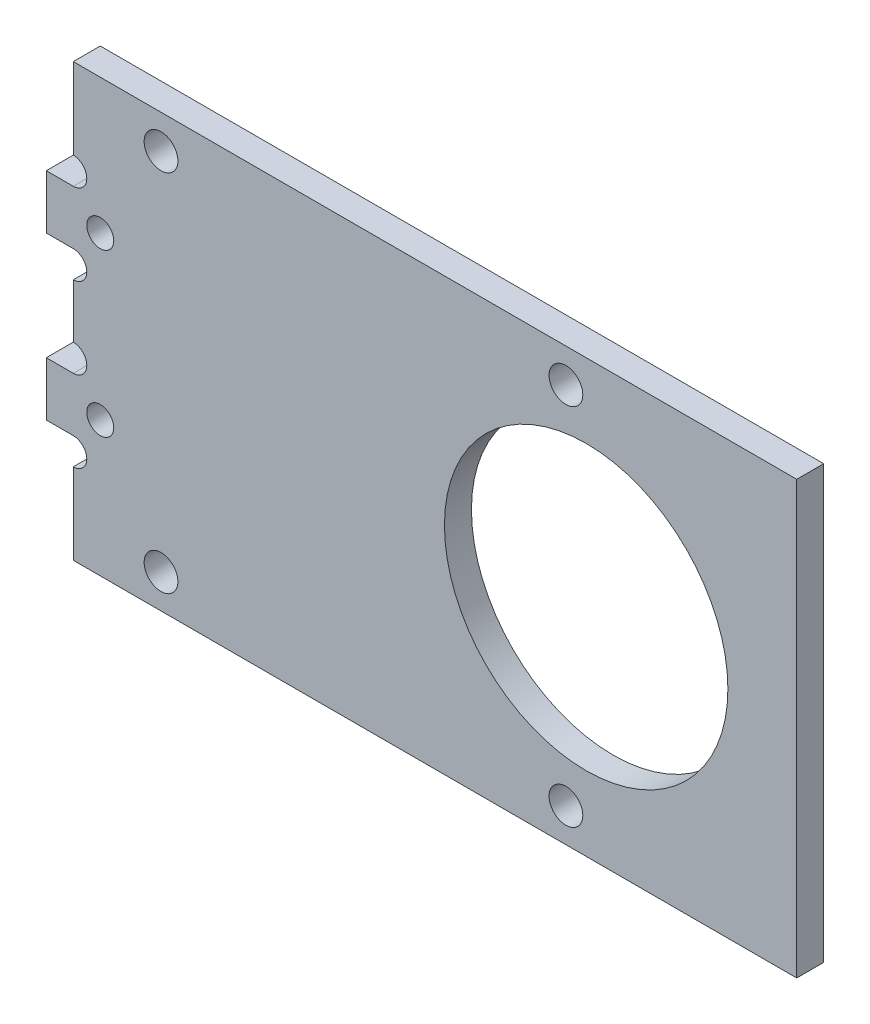
SolidWorks part; units mm, degrees
material "自訂玻璃纖維"
ref_plane "前基準面" through (0, 0, 0) normal (0, 0, 1) x (1, 0, 0)
ref_plane "上基準面" through (0, 0, 0) normal (0, 1, 0) x (1, 0, 0)
ref_plane "右基準面" through (0, 0, 0) normal (1, 0, 0) x (0, 0, -1)
sketch "草圖1" plane through (0, 0, 0) normal (0, 0, 1) x (1, 0, 0)
  line L0 (-8.8684, 14.8937) -> (-8.8684, 15.8937)
  line L1 (-7.8684, 15.8937) -> (43.7816, 15.8937)
  line L2 (-8.8684, 14.8937) -> (-8.8684, 9.8937)
  line L3 (-7.8684, -16.1063) -> (43.7816, -16.1063)
  line L4 (44.7316, 14.8937) -> (44.7316, -15.1063)
  line L5 (-8.8684, 15.8937) -> (-7.8684, 15.8937)
  line L6 (44.7316, 14.8937) -> (44.7316, 15.8937)
  line L7 (44.7316, 15.8937) -> (43.7816, 15.8937)
  line L8 (44.7316, -15.1063) -> (44.7316, -16.1063)
  line L9 (44.7316, -16.1063) -> (43.7816, -16.1063)
  line L10 (-8.8684, -15.1063) -> (-8.8684, -16.1063)
  line L11 (-8.8684, -16.1063) -> (-7.8684, -16.1063)
  line L12 (-8.8684, 1.8937) -> (-8.8684, -2.1063)
  line L13 (-8.8684, 7.8937) -> (-10.8684, 7.8937)
  line L14 (-8.8684, -8.1063) -> (-10.8684, -8.1063)
  line L15 (-8.8684, 3.8937) -> (-10.8684, 3.8937)
  line L16 (-10.8684, 7.8937) -> (-10.8684, 3.8937)
  line L17 (-8.8684, -4.1063) -> (-10.8684, -4.1063)
  line L18 (-10.8684, -4.1063) -> (-10.8684, -8.1063)
  line L19 (-8.8684, -10.1063) -> (-8.8684, -15.1063)
  arc A0 (-8.8684, 7.8937) -> (-8.8684, 9.8937) centre (-8.8684, 8.8937) ccw
  circle A1 centre (-6.8684, 5.8937) radius 1
  circle A2 centre (-6.8684, -6.1063) radius 1
  arc A3 (-8.8684, 3.8937) -> (-8.8684, 1.8937) centre (-8.8684, 2.8937) cw
  arc A4 (-8.8684, -8.1063) -> (-8.8684, -10.1063) centre (-8.8684, -9.1063) cw
  arc A5 (-8.8684, -4.1063) -> (-8.8684, -2.1063) centre (-8.8684, -3.1063) ccw
  circle A6 centre (-2.3684, 13.3937) radius 1.25
  circle A7 centre (-2.3684, -13.6063) radius 1.25
  circle A8 centre (27.6316, 13.3937) radius 1.25
  circle A9 centre (27.6316, -13.6063) radius 1.25
  circle A10 centre (29.1316, -0.1063) radius 10.5
  point P10 (-8.8684, -16.1063)
  point P15 (44.7316, 15.8937)
  point P18 (-8.8684, 15.8937)
  dimension "D2" = 53.6
  dimension "D3" = 2
  dimension "D4" = 4
  dimension "D5" = 12
  dimension "D7" = 2
  dimension "D11" = 2.5
  dimension "D12" = 27
  dimension "D13" = 2.5
  dimension "D15" = 21
  dimension "D16" = 30
  dimension "D17" = 27
  dimension "D18" = 2.5
  dimension "D19" = 30
  dimension "D20" = 1.5
  dimension "D6" = 2
  dimension "D1" = 32
extrude "填料-伸長1" add sketch "草圖1" along normal blind 2
